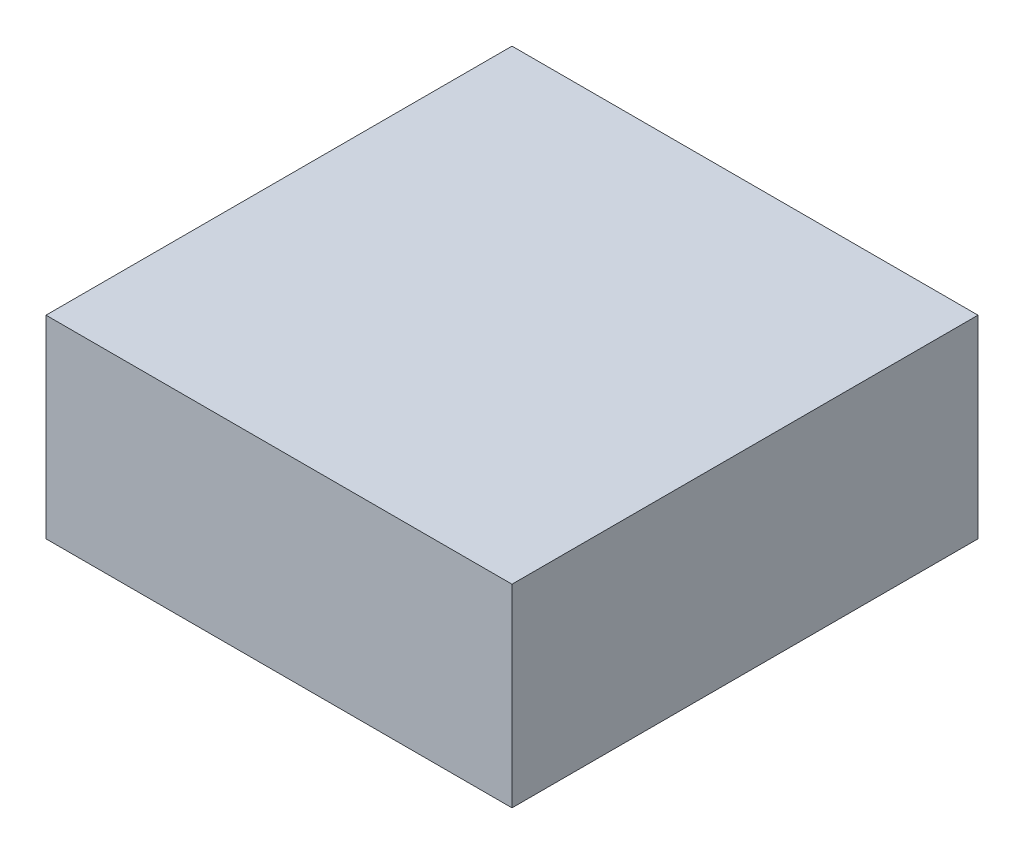
SolidWorks part; units mm, degrees
ref_plane "Front Plane" through (0, 0, 0) normal (0, 0, 1) x (1, 0, 0)
ref_plane "Top Plane" through (0, 0, 0) normal (0, 1, 0) x (1, 0, 0)
ref_plane "Right Plane" through (0, 0, 0) normal (1, 0, 0) x (0, 0, -1)
sketch "Sketch1" plane through (0, 0, 0) normal (0, 1, 0) x (1, 0, 0)
  line L1 (0, 0) -> (43.3, 0)
  line L2 (0, 0) -> (0, 43.3)
  line L3 (0, 43.3) -> (43.3, 43.3)
  line L4 (43.3, 0) -> (43.3, 43.3)
  dimension "D1" = 43.3
  dimension "D2" = 43.3
extrude "Boss-Extrude1" add sketch "Sketch1" along normal blind 18
